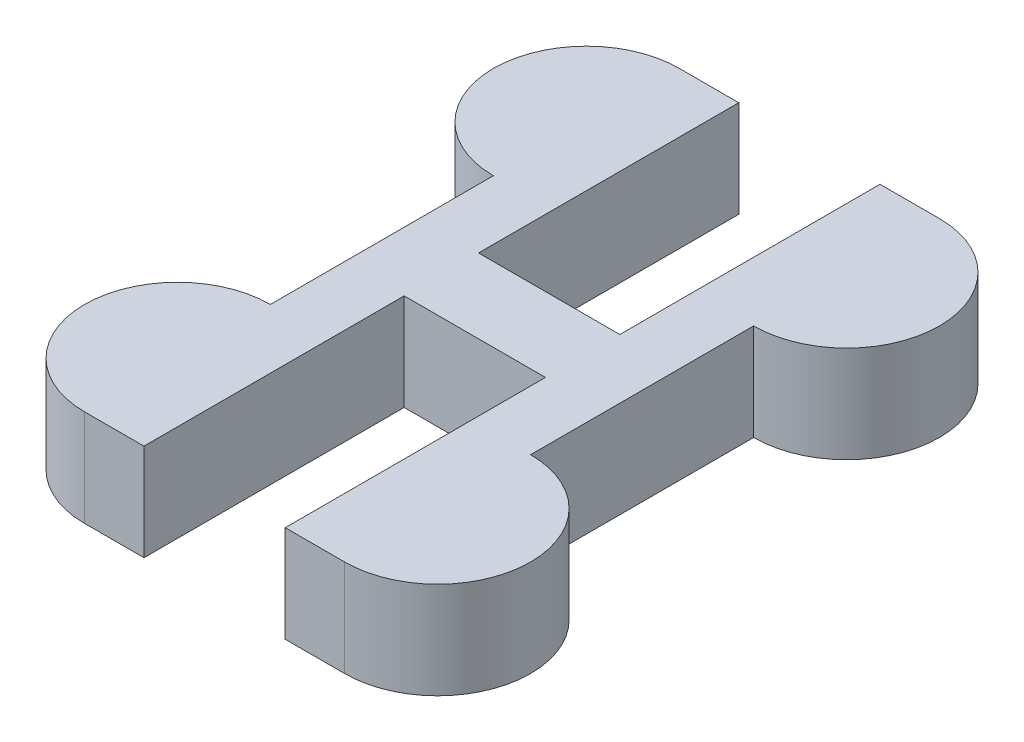
SolidWorks part; units mm, degrees
ref_plane "Front Plane" through (0, 0, 0) normal (0, 0, 1) x (1, 0, 0)
ref_plane "Top Plane" through (0, 0, 0) normal (0, 1, 0) x (1, 0, 0)
ref_plane "Right Plane" through (0, 0, 0) normal (1, 0, 0) x (0, 0, -1)
sketch "Sketch1" plane through (0, 0, 0) normal (0, 1, 0) x (1, 0, 0)
  line L0 (-0.95, 4) -> (-0.95, 0.5)
  line L1 (-1.75, -4) -> (-0.95, -4)
  line L2 (-1.75, -1.5) -> (-1.75, 1.5)
  line L3 (-1.75, 4) -> (-0.95, 4)
  line L4 (1.75, -1.5) -> (1.75, 1.5)
  line L5 (-1.75, -4) -> (1.75, 4) construction
  line L6 (-1.75, 4) -> (1.75, -4) construction
  line L7 (-0.95, 0.5) -> (0.95, 0.5)
  line L8 (0.95, 0.5) -> (0.95, 4)
  line L9 (0.95, 4) -> (1.75, 4)
  line L10 (0.95, -4) -> (1.75, -4)
  line L11 (0.95, -4) -> (0.95, -0.5)
  line L12 (0.95, -0.5) -> (-0.95, -0.5)
  line L13 (-0.95, -0.5) -> (-0.95, -4)
  line L14 (-1.75, 4) -> (-1.75, 1.5) construction
  line L15 (-1.75, -1.5) -> (-1.75, -4) construction
  line L16 (1.75, -4) -> (1.75, -1.5) construction
  line L17 (1.75, 1.5) -> (1.75, 4) construction
  arc A0 (-1.75, 4) -> (-1.75, 1.5) centre (-1.75, 2.75) ccw
  arc A1 (1.75, 1.5) -> (1.75, 4) centre (1.75, 2.75) ccw
  arc A2 (-1.75, -1.5) -> (-1.75, -4) centre (-1.75, -2.75) ccw
  arc A3 (1.75, -4) -> (1.75, -1.5) centre (1.75, -2.75) ccw
  point P8 (0, 0)
  point P24 (-1.75, 2.75)
  point P25 (1.75, 2.75)
  dimension "D1" = 8
  dimension "Diameter" = 2.5
  dimension "D2" = 3.5
  dimension "D4" = 0.8
  dimension "D5" = 1
extrude "Boss-Extrude1" add sketch "Sketch1" along normal blind 1.3
